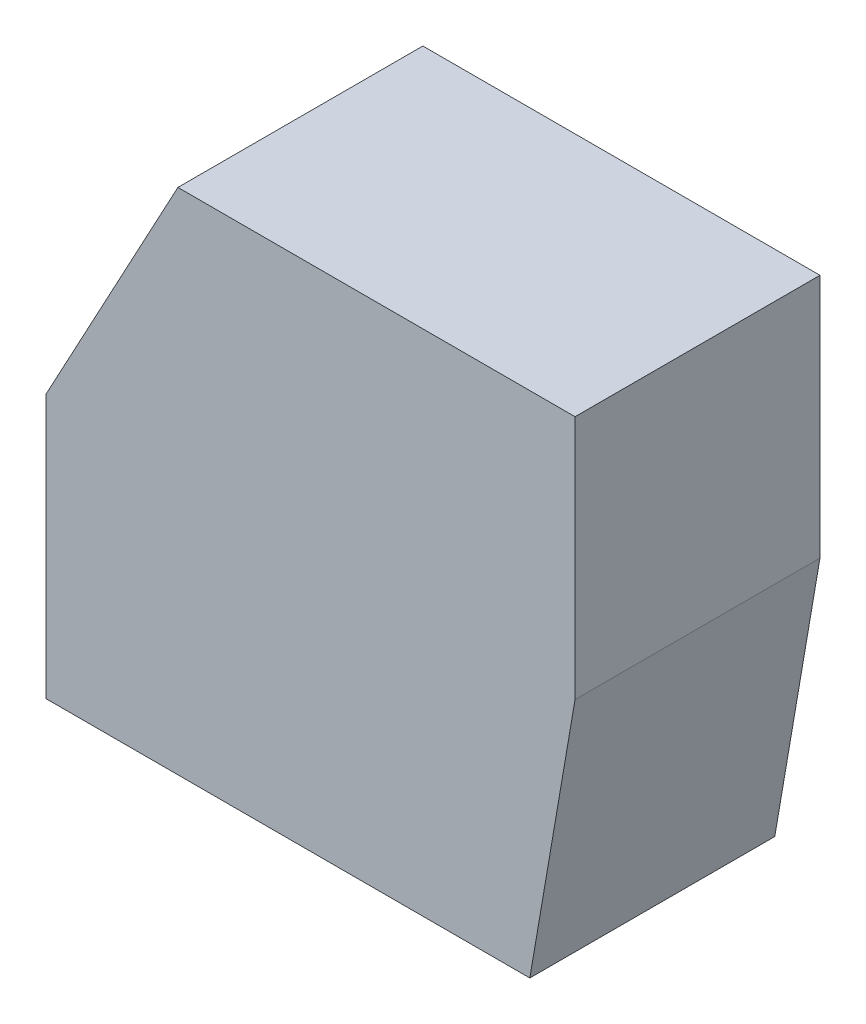
SolidWorks part; units mm, degrees
ref_plane "Ebene vorne" through (0, 0, 0) normal (0, 0, 1) x (1, 0, 0)
ref_plane "Ebene oben" through (0, 0, 0) normal (0, 1, 0) x (1, 0, 0)
ref_plane "Ebene rechts" through (0, 0, 0) normal (1, 0, 0) x (0, 0, -1)
sketch "Skizze1" plane through (0, 0, 0) normal (0, 0, 1) x (1, 0, 0)
  line L0 (0, -35) -> (6.4333, -35) construction
  line L5 (0, 100) -> (-35, 35)
  line L6 (-35, -35) -> (35, -35)
  line L7 (0, -35) -> (40.3912, -35)
  line L8 (82.3912, -35) -> (40.3912, -35)
  line L14 (40.3912, -35) -> (82.3912, -35)
  line L16 (82.3912, -35) -> (93.3912, -35)
  line L17 (105.3912, 35) -> (93.3912, -35)
  line L26 (0, 100) -> (105.3912, 100)
  line L27 (105.3912, 35) -> (105.3912, 100)
  line L37 (105.3912, 35) -> (105.3912, 100)
  line L38 (105.3912, 100) -> (71.3912, 100)
  line L42 (-35, -35) -> (-35, 35)
  point P15 (61.3912, -23.5)
  point P19 (41.1956, 21)
  point P23 (52.6956, 67.5)
  point P25 (88.7388, -5.3941)
  point P29 (88.3912, 67.5)
  dimension "D2" = 70
  dimension "D6" = 65
  dimension "D9" = 11
extrude "Aufsatz-Linear austragen1" add sketch "Skizze1" along normal blind 65 contours L42 L6 L7 L8 L16 L17 L27 L26 L5
